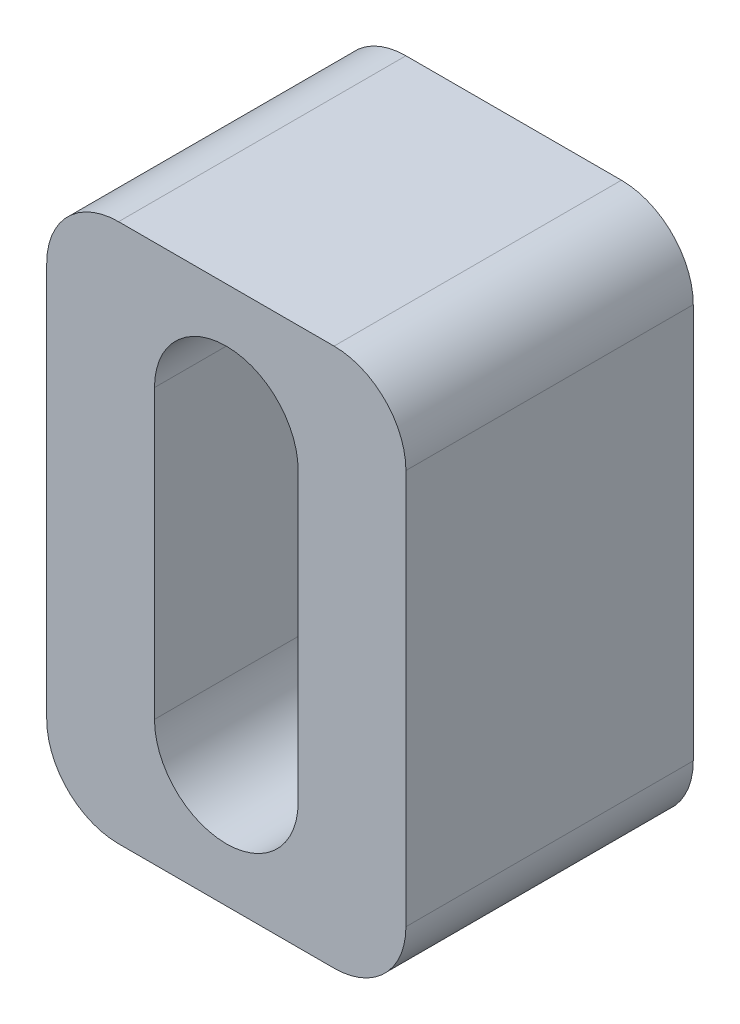
SolidWorks part; units mm, degrees
ref_plane "Front Plane" through (0, 0, 0) normal (0, 0, 1) x (1, 0, 0)
ref_plane "Top Plane" through (0, 0, 0) normal (0, 1, 0) x (1, 0, 0)
ref_plane "Right Plane" through (0, 0, 0) normal (1, 0, 0) x (0, 0, -1)
sketch "Sketch1" plane through (0, 0, 0) normal (0, 0, 1) x (1, 0, 0)
  line L0 (5, 3.5) -> (5, 11.5) construction
  line L1 (0, 0) -> (10, 0)
  line L2 (0, 0) -> (0, 15)
  line L3 (0, 15) -> (10, 15)
  line L4 (10, 0) -> (10, 15)
  line L5 (3, 3.5) -> (3, 11.5)
  line L6 (7, 3.5) -> (7, 11.5)
  arc A0 (3, 3.5) -> (7, 3.5) centre (5, 3.5) ccw
  arc A1 (7, 11.5) -> (3, 11.5) centre (5, 11.5) ccw
  point P7 (5, 7.5)
  point P12 (4.6153, 7.9297)
  point P13 (5.8784, 4.8717)
  point P14 (5.9449, 9.5584)
  dimension "D3" = 2
  dimension "D1" = 10
  dimension "D2" = 15
  dimension "D4" = 5
  dimension "D5" = 8
  dimension "D6" = 3.5
extrude "Boss-Extrude1" add sketch "Sketch1" along normal blind 8
fillet "Fillet1" radius 2 4 edges at (0, 0, 4) (10, 0, 4) (10, 15, 4) (0, 15, 4)
